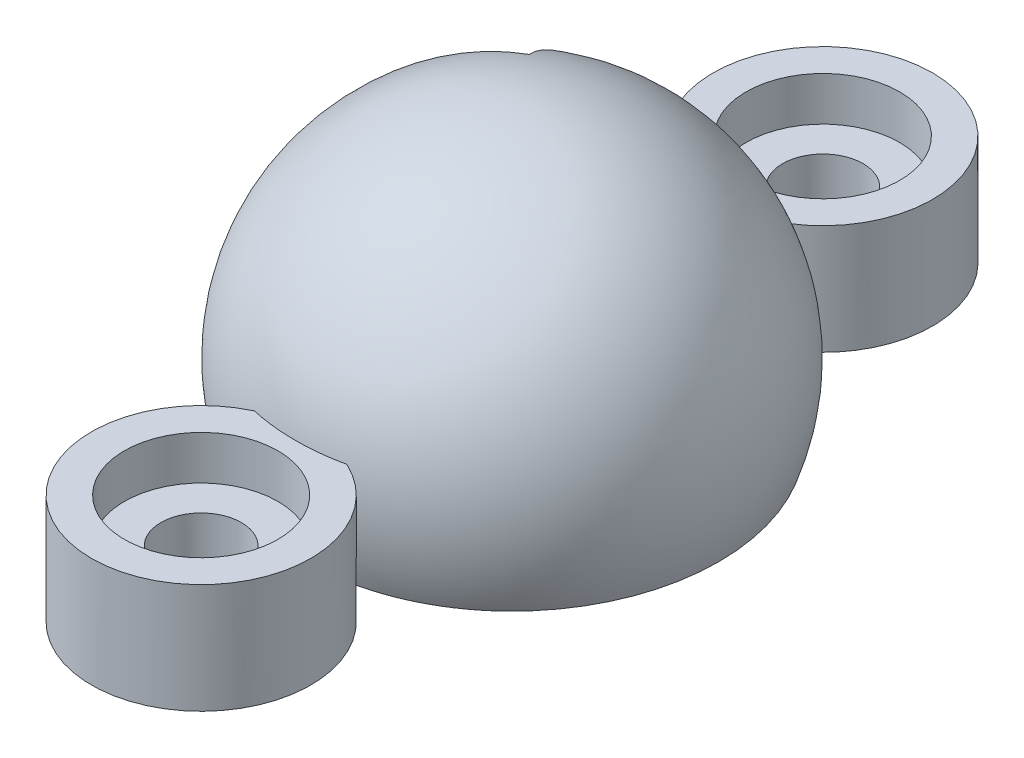
SolidWorks part; units mm, degrees
other "Compression Link 1 Fixed Ball Retainer"
other "Compression Link 1 Fixed Ball Retainer Left"
ref_plane "Front Plane" through (0, 0, 0) normal (0, 0, 1) x (1, 0, 0)
ref_plane "Top Plane" through (0, 0, 0) normal (0, 1, 0) x (1, 0, 0)
ref_plane "Right Plane" through (0, 0, 0) normal (1, 0, 0) x (0, 0, -1)
sketch3d "Retainer Feature 1 axis line"
  line L0 (-26.2917, -73, -10) -> (-26.2917, -73, 10) construction
ref_axis "Retainer Feature 1 axis" through (-26.2917, -73, -10) along (0, 0, 1)
sketch3d "Retainer Feature 1 profile datum points"
  point P0 (-26.2917, -73, 0)
  point P1 (-16.2917, -73, 0)
  point P2 (-26.2917, -73, 10)
ref_plane "Retainer Feature 1 profile plane" through (0, -73, 0) normal (0, -1, 0) x (-1, 0, 0)
sketch "Retainer Feature 1 profile" plane through (0, -73, 0) normal (0, -1, 0) x (-1, 0, 0)
  line L0 (26.2917, -6) -> (26.2917, 6)
  arc A0 (26.2917, 6) -> (26.2917, -6) centre (26.2917, 0) ccw
revolve "Retainer Feature 1" add sketch "Retainer Feature 1 profile" angle 360 about axis through (-26.2917, -73, -10) along (0, 0, 1)
sketch3d "Retainer Feature 2 profile datum points"
  point P0 (-33.2917, -71, -7)
  point P1 (-23.2917, -71, -7)
  point P2 (-33.2917, -61, -7)
ref_plane "Retainer Feature 2 profile plane" through (0, 0, -7) normal (0, 0, 1) x (1, 0, 0)
sketch "Retainer Feature 2 profile" plane through (0, 0, -7) normal (0, 0, 1) x (1, 0, 0)
  line L0 (-33.2917, -71) -> (-19.2917, -71)
  line L1 (-19.2917, -71) -> (-19.2917, -66)
  line L2 (-19.2917, -66) -> (-33.2917, -66)
  line L3 (-33.2917, -66) -> (-33.2917, -71)
extrude "Retainer Feature 2" cut sketch "Retainer Feature 2 profile" along normal blind 14
sketch3d "Retainer Feature 3 profile datum points"
  point P0 (-26.2917, -71, -8.5)
  point P1 (-16.2917, -71, -8.5)
  point P2 (-26.2917, -71, 1.5)
ref_plane "Retainer Feature 3 profile plane" through (0, -71, 0) normal (0, -1, 0) x (-1, 0, 0)
sketch "Retainer Feature 3 profile" plane through (0, -71, 0) normal (0, -1, 0) x (-1, 0, 0)
  circle A0 centre (26.2917, 8.5) radius 3
extrude "Retainer Feature 3" add sketch "Retainer Feature 3 profile" along normal blind 3
sketch3d "Retainer Feature 4 profile datum points"
  point P0 (-26.2917, -71, 8.5)
  point P1 (-16.2917, -71, 8.5)
  point P2 (-26.2917, -71, 18.5)
ref_plane "Retainer Feature 4 profile plane" through (0, -71, 0) normal (0, -1, 0) x (-1, 0, 0)
sketch "Retainer Feature 4 profile" plane through (0, -71, 0) normal (0, -1, 0) x (-1, 0, 0)
  circle A0 centre (26.2917, -8.5) radius 3
extrude "Retainer Feature 4" add sketch "Retainer Feature 4 profile" along normal blind 3
sketch3d "Retainer Feature 5 axis line"
  line L0 (-26.2917, -73, -10) -> (-26.2917, -73, 10) construction
ref_axis "Retainer Feature 5 axis" through (-26.2917, -73, -10) along (0, 0, 1)
sketch3d "Retainer Feature 5 profile datum points"
  point P0 (-26.2917, -73, 0)
  point P1 (-16.2917, -73, 0)
  point P2 (-26.2917, -73, 10)
ref_plane "Retainer Feature 5 profile plane" through (0, -73, 0) normal (0, -1, 0) x (-1, 0, 0)
sketch "Retainer Feature 5 profile" plane through (0, -73, 0) normal (0, -1, 0) x (-1, 0, 0)
  line L0 (26.2917, -3.15) -> (26.2917, 3.15)
  arc A0 (26.2917, 3.15) -> (26.2917, -3.15) centre (26.2917, 0) ccw
revolve "Retainer Feature 5" cut sketch "Retainer Feature 5 profile" angle 360 about axis through (-26.2917, -73, -10) along (0, 0, 1)
sketch3d "Retainer Feature 6 profile datum points"
  point P0 (-26.2917, -70, -8.5)
  point P1 (-16.2917, -70, -8.5)
  point P2 (-26.2917, -70, 1.5)
ref_plane "Retainer Feature 6 profile plane" through (0, -70, 0) normal (0, -1, 0) x (-1, 0, 0)
sketch "Retainer Feature 6 profile" plane through (0, -70, 0) normal (0, -1, 0) x (-1, 0, 0)
  circle A0 centre (26.2917, 8.5) radius 1.1
extrude "Retainer Feature 6" cut sketch "Retainer Feature 6 profile" along normal blind 4.25
sketch3d "Retainer Feature 7 profile datum points"
  point P0 (-26.2917, -72.8, -8.5)
  point P1 (-16.2917, -72.8, -8.5)
  point P2 (-26.2917, -72.8, 1.5)
ref_plane "Retainer Feature 7 profile plane" through (0, -72.8, 0) normal (0, -1, 0) x (-1, 0, 0)
sketch "Retainer Feature 7 profile" plane through (0, -72.8, 0) normal (0, -1, 0) x (-1, 0, 0)
  circle A0 centre (26.2917, 8.5) radius 2.1
extrude "Retainer Feature 7" cut sketch "Retainer Feature 7 profile" along normal blind 1.45
sketch3d "Retainer Feature 8 profile datum points"
  point P0 (-26.2917, -70, 8.5)
  point P1 (-16.2917, -70, 8.5)
  point P2 (-26.2917, -70, 18.5)
ref_plane "Retainer Feature 8 profile plane" through (0, -70, 0) normal (0, -1, 0) x (-1, 0, 0)
sketch "Retainer Feature 8 profile" plane through (0, -70, 0) normal (0, -1, 0) x (-1, 0, 0)
  circle A0 centre (26.2917, -8.5) radius 1.1
extrude "Retainer Feature 8" cut sketch "Retainer Feature 8 profile" along normal blind 4.25
sketch3d "Retainer Feature 9 profile datum points"
  point P0 (-26.2917, -72.8, 8.5)
  point P1 (-16.2917, -72.8, 8.5)
  point P2 (-26.2917, -72.8, 18.5)
ref_plane "Retainer Feature 9 profile plane" through (0, -72.8, 0) normal (0, -1, 0) x (-1, 0, 0)
sketch "Retainer Feature 9 profile" plane through (0, -72.8, 0) normal (0, -1, 0) x (-1, 0, 0)
  circle A0 centre (26.2917, -8.5) radius 2.1
extrude "Retainer Feature 9" cut sketch "Retainer Feature 9 profile" along normal blind 1.45
sketch3d "Middle Right Fixed Compression Ball Retainer 1 Angular Clearance Sketch 21 datum points"
  point P0 (-26.2917, -73, 0)
  point P1 (-20.2307, -78.3859, -5.853)
  point P2 (-24.834, -79.4818, 7.474)
ref_plane "Middle Right Fixed Compression Ball Retainer 1 Angular Clearance Sketch 21 plane" through (-46.8018, -32.2203, -18.8155) normal (-0.7819, -0.5383, -0.3144) x (-0.2589, -0.1783, 0.9493)
sketch "Middle Right Fixed Compression Ball Retainer 1 Angular Clearance Sketch 21" plane through (-46.8018, -32.2203, -18.8155) normal (-0.7819, -0.5383, -0.3144) x (-0.2589, -0.1783, 0.9493)
  line L0 (20.2973, -41.529) -> (16.3514, -46.5678)
  line L1 (16.3514, -46.5678) -> (19.3432, -48.9107)
  line L2 (19.3432, -48.9107) -> (23.2891, -43.8719)
  line L3 (23.2891, -43.8719) -> (20.2973, -41.529)
extrude "Retainer Feature 12" cut sketch "Middle Right Fixed Compression Ball Retainer 1 Angular Clearance Sketch 21" along normal blind 10
sketch3d "Mirror1 profile datum points"
  point P0 (0, 0, 0)
  point P1 (10, 0, 0)
  point P2 (0, 0, 10)
ref_plane "Mirror1 profile plane" through (0, 0, 0) normal (0, -1, 0) x (-1, 0, 0)
mirror "Mirror1" about plane through (0, 0, 0) normal (0, -1, 0) of bodies 110
delete or keep bodies "Remove1" type delete bodies bodies 110
